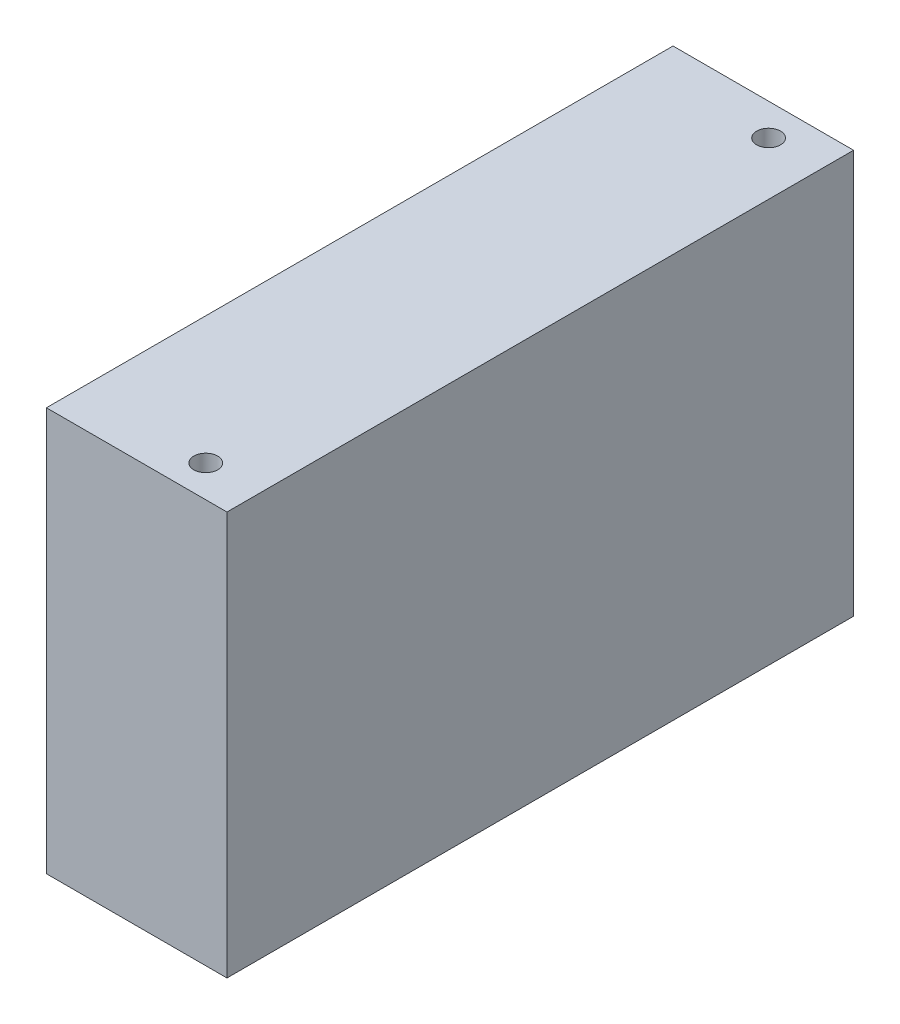
SolidWorks part; units mm, degrees
ref_plane "前视基准面" through (0, 0, 0) normal (0, 0, 1) x (1, 0, 0)
ref_plane "上视基准面" through (0, 0, 0) normal (0, 1, 0) x (1, 0, 0)
ref_plane "右视基准面" through (0, 0, 0) normal (1, 0, 0) x (0, 0, -1)
sketch "草图1" plane through (0, 0, 0) normal (0, 1, 0) x (1, 0, 0)
  line L1 (-17, -59) -> (17, -59)
  line L2 (-17, -59) -> (-17, 59)
  line L3 (-17, 59) -> (17, 59)
  line L4 (17, -59) -> (17, 59)
  line L5 (0, 59) -> (0, -59) construction
  line L6 (-17, 0) -> (17, 0) construction
  point P0 (0, 0)
  dimension "D1" = 34
  dimension "D2" = 118
extrude "凸台-拉伸1" add sketch "草图1" along normal blind 76
sketch "草图2" plane through (0, 0, 0) normal (0, -1, 0) x (1, 0, 0)
  line L0 (17, 59) -> (17, -59) construction
  line L1 (-17, 59) -> (17, 59) construction
  line L2 (-21.4539, 0) -> (22.2754, 0) construction
  circle A0 centre (7, 53) radius 2.25
  circle A1 centre (7, -53) radius 2.25
  dimension "D3" = 4.5
  dimension "D1" = 10
  dimension "D2" = 6
extrude "切除-拉伸1" cut sketch "草图2" against normal through all
